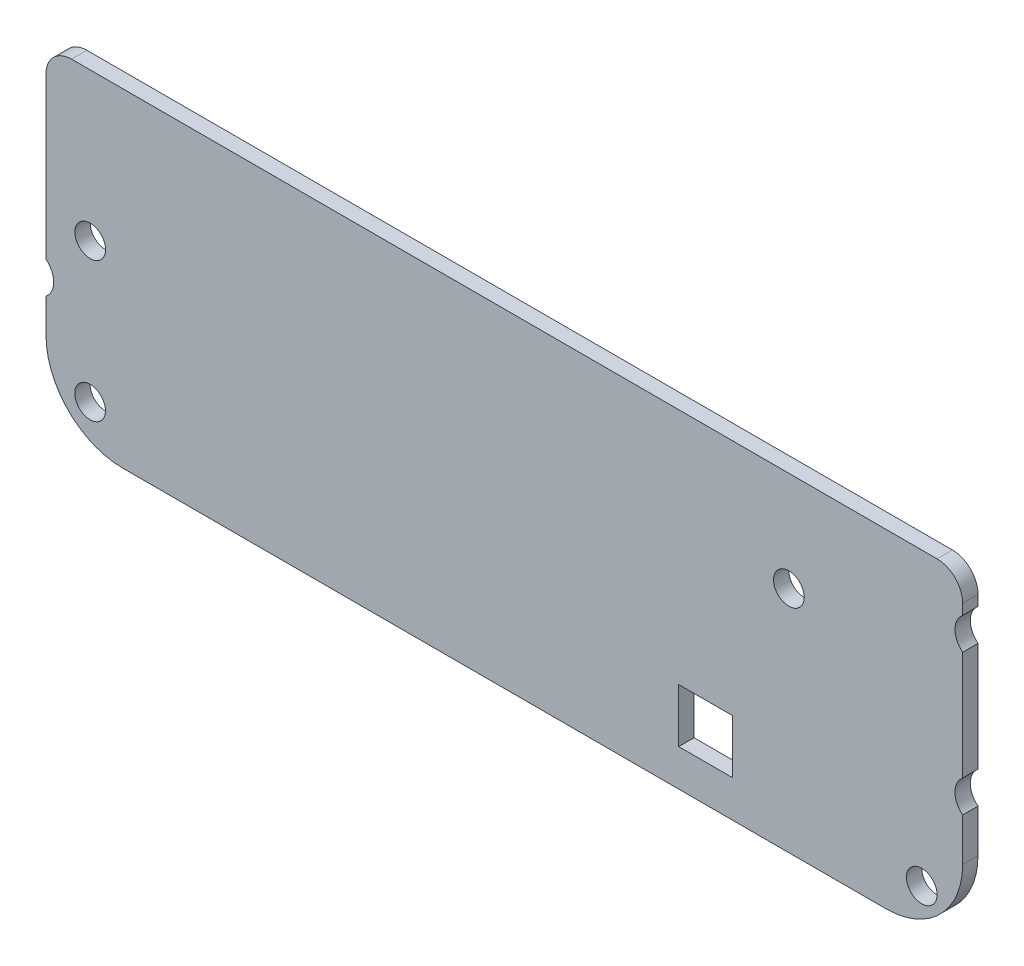
SolidWorks part; units mm, degrees
ref_plane "Plan de face" through (0, 0, 0) normal (0, 0, 1) x (1, 0, 0)
ref_plane "Plan de dessus" through (0, 0, 0) normal (0, 1, 0) x (1, 0, 0)
ref_plane "Plan de droite" through (0, 0, 0) normal (1, 0, 0) x (0, 0, -1)
sketch "Esquisse1" plane through (0, 0, 0) normal (0, 0, 1) x (1, 0, 0)
  line L1 (118.1017, 78.4023) -> (267.2717, 78.4023)
  line L2 (103.1017, 93.4023) -> (103.1017, 137.6323)
  line L3 (108.1017, 142.6323) -> (277.2717, 142.6323)
  line L4 (282.2717, 93.4023) -> (282.2717, 137.6323)
  arc A0 (277.2717, 142.6323) -> (282.2717, 137.6323) centre (277.2717, 137.6323) cw
  arc A1 (103.1017, 137.6323) -> (108.1017, 142.6323) centre (108.1017, 137.6323) cw
  arc A2 (267.2717, 78.4023) -> (282.2717, 93.4023) centre (267.2717, 93.4023) ccw
  arc A3 (118.1017, 78.4023) -> (103.1017, 93.4023) centre (118.1017, 93.4023) cw
  point P6 (282.2717, 142.6323)
  point P9 (103.1017, 142.6323)
  point P12 (282.2717, 78.4023)
  point P19 (192.6867, 110.5173)
  dimension "D3" = 5
  dimension "D4" = 15
  dimension "D1" = 179.17
  dimension "D2" = 64.23
extrude "Boss.-Extru.1" add sketch "Esquisse1" along normal blind 3
sketch "Esquisse2" plane through (0, 0, 0) normal (0, 0, -1) x (-1, 0, 0)
  line L0 (-103.1017, 137.6323) -> (-103.1017, 93.4023) construction
  line L1 (-118.1017, 78.4023) -> (-267.2717, 78.4023) construction
  line L2 (-282.2717, 93.4023) -> (-282.2717, 137.6323) construction
  line L3 (-277.2717, 142.6323) -> (-108.1017, 142.6323) construction
  circle A0 centre (-111.7417, 113.6923) radius 3
  circle A1 centre (-111.7217, 86.4023) radius 3
  circle A2 centre (-248.3017, 123.1223) radius 3
  circle A3 centre (-274.2717, 85.7523) radius 3
  dimension "D1" = 8.62
  dimension "D2" = 8
  dimension "D3" = 7.35
  dimension "D4" = 8
  dimension "D5" = 19.51
  dimension "D6" = 33.97
  dimension "D7" = 8.64
  dimension "D8" = 28.94
extrude "Enlèv. mat.-Extru.1" cut sketch "Esquisse2" against normal blind 10
sketch "Esquisse7" plane through (0, 0, 3) normal (0, 0, 1) x (1, 0, 0)
  line L0 (128.0704, 78.4023) -> (128.0704, 103.1223)
  line L1 (118.1017, 78.4023) -> (267.2717, 78.4023) construction
  line L2 (128.0704, 103.1223) -> (103.1017, 103.1223)
  line L3 (103.1017, 137.6323) -> (103.1017, 93.4023) construction
  line L4 (103.1017, 103.1223) -> (98.1017, 103.1223)
  line L5 (263.0387, 78.4023) -> (263.0387, 104.9023)
  line L6 (263.0387, 104.9023) -> (282.2717, 104.9023)
  line L7 (282.2717, 93.4023) -> (282.2717, 137.6323) construction
  line L8 (282.2717, 104.9023) -> (287.2717, 104.9023)
  line L9 (263.7381, 142.6323) -> (263.7381, 132.4423)
  line L10 (277.2717, 142.6323) -> (108.1017, 142.6323) construction
  line L11 (263.7381, 132.4423) -> (282.2717, 132.4423)
  line L12 (282.2717, 132.4423) -> (287.2717, 132.4423)
  circle A0 centre (100.6017, 103.1223) radius 4
  circle A1 centre (284.7717, 104.9023) radius 4
  circle A2 centre (284.7717, 132.4423) radius 4
extrude "Enlèv. mat.-Extru.2" cut sketch "Esquisse7" against normal blind 10
sketch "Esquisse8" plane through (0, 0, 0) normal (0, 0, -1) x (-1, 0, 0)
  line L0 (-282.2717, 93.4023) -> (-282.2717, 101.7798) construction
  line L1 (-237.2717, 85.6023) -> (-226.7717, 85.6023)
  line L2 (-237.2717, 85.6023) -> (-237.2717, 96.1023)
  line L3 (-237.2717, 96.1023) -> (-226.7717, 96.1023)
  line L4 (-226.7717, 85.6023) -> (-226.7717, 96.1023)
  line L5 (-118.1017, 78.4023) -> (-267.2717, 78.4023) construction
  dimension "D1" = 10.5
  dimension "D2" = 10.5
  dimension "D3" = 45
  dimension "D4" = 7.2
extrude "Enlèv. mat.-Extru.3" cut sketch "Esquisse8" against normal blind 10
